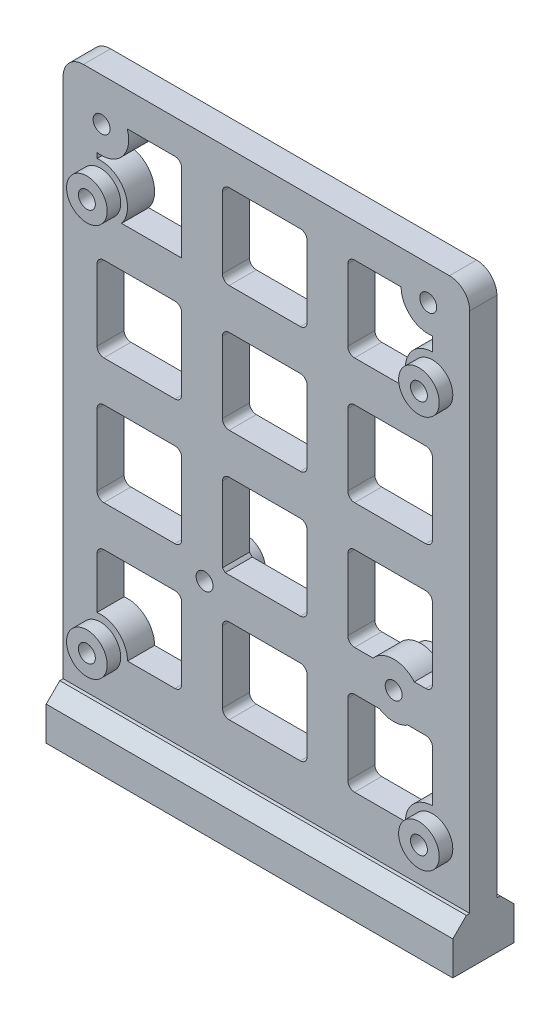
SolidWorks part; units mm, degrees
ref_plane "Спереди" through (0, 0, 0) normal (0, 0, 1) x (1, 0, 0)
ref_plane "Сверху" through (0, 0, 0) normal (0, 1, 0) x (1, 0, 0)
ref_plane "Справа" through (0, 0, 0) normal (1, 0, 0) x (0, 0, -1)
sketch "Sketch1" plane through (0, 0, 0) normal (0, 0, 1) x (1, 0, 0)
  line L1 (-30, 40) -> (30, 40)
  line L2 (-30, 40) -> (-30, -40)
  line L3 (-30, -40) -> (30, -40)
  line L4 (30, 40) -> (30, -40)
  line L5 (-30, 40) -> (30, -40) construction
  line L6 (-30, -40) -> (30, 40) construction
  point P0 (0, 0)
  dimension "D1" = 80
  dimension "D2" = 60
extrude "Boss-Extrude1" add sketch "Sketch1" along normal blind 4
sketch "Sketch2" plane through (0, 0, 4) normal (0, 0, 1) x (1, 0, 0)
  line L0 (0, 17.2836) -> (0, -4) construction
  line L1 (0, -4) -> (-11.1351, -4) construction
  line L2 (30, 40) -> (-30, 40) construction
  circle A0 centre (-24.5, 25) radius 1.25
  circle A1 centre (24.5, 25) radius 1.25
  circle A2 centre (24.5, -33) radius 1.25
  circle A3 centre (-24.5, -33) radius 1.25
  point P12 (-24.5, 32.5822)
  dimension "D1" = 58
  dimension "D2" = 49
  dimension "D3" = 2.5
  dimension "D4" = 15
extrude "Cut-Extrude1" cut sketch "Sketch2" against normal through all
sketch "Sketch3" plane through (0, 0, 4) normal (0, 0, 1) x (1, 0, 0)
  circle A0 centre (-24.5, 25) radius 3
  circle A1 centre (24.5, 25) radius 3
  circle A2 centre (24.5, -33) radius 3
  circle A3 centre (-24.5, -33) radius 3
  point P5 (24.5, 32.5)
  point P9 (24.5, -25.5)
  point P13 (-24.5, -25.5)
  circle M5 centre (-24.5, -33) radius 1.25
  circle M6 centre (24.5, -33) radius 1.25
  circle M7 centre (24.5, 25) radius 1.25
  circle M8 centre (-24.5, 25) radius 1.25
  dimension "D1" = 6
extrude "Boss-Extrude2" add sketch "Sketch3" along normal blind 2 contours A0 M8 | A1 M7 | A2 M6 | A3 M5
sketch "Sketch4" plane through (0, 0, 0) normal (0, 0, -1) x (-1, 0, 0)
  line L1 (-30, 40) -> (30, 40) construction
  circle A0 centre (-18.7727, -17.1) radius 1.25
  circle A1 centre (9.1273, -17.1) radius 1.25
  circle A2 centre (-23.8727, 35) radius 1.25
  circle A3 centre (24.3273, 33.7) radius 1.25
  point P4 (23.4203, 17.4097)
  point P9 (9.1273, -30.7292)
  dimension "D1" = 2.5
  dimension "D2" = 2.5
  dimension "D3" = 27.9
  dimension "D4" = 2.5
  dimension "D5" = 5.1
  dimension "D7" = 2.5
  dimension "D6" = 52.1
  dimension "D8" = 1.3
  dimension "D9" = 15.2
  dimension "D10" = 5
extrude "Cut-Extrude2" cut sketch "Sketch4" against normal through all
sketch "Sketch5" plane through (0, 0, 0) normal (0, 0, -1) x (-1, 0, 0)
  circle A0 centre (-23.8727, 35) radius 3
  circle A1 centre (24.3273, 33.7) radius 3
  circle A2 centre (-18.7727, -17.1) radius 3
  circle A3 centre (9.1273, -17.1) radius 3
  circle M1 centre (24.3273, 33.7) radius 1.25
  circle M2 centre (-23.8727, 35) radius 1.25
  circle M3 centre (9.1273, -17.1) radius 1.25
  circle M4 centre (-18.7727, -17.1) radius 1.25
  dimension "D1" = 6
  dimension "D2" = 6
  dimension "D3" = 6
  dimension "D4" = 6
extrude "Boss-Extrude3" add sketch "Sketch5" along normal blind 2 contours A0 M2 | A1 M1 | A3 M3 | A2 M4
sketch "Sketch7" plane through (0, 0, 4) normal (0, 0, 1) x (1, 0, 0)
  line L0 (-30, 40) -> (-30, -40) construction
  line L1 (-25, 35) -> (-12.5, 35)
  line L2 (-25, 35) -> (-25, 22.5)
  line L3 (-25, 22.5) -> (-12.5, 22.5)
  line L4 (-12.5, 35) -> (-12.5, 22.5)
  line L5 (30, 40) -> (-30, 40) construction
  line L6 (-6.5, 35) -> (-6.5, 22.5)
  line L7 (-6.5, 35) -> (6, 35)
  line L8 (6, 35) -> (6, 22.5)
  line L9 (-6.5, 22.5) -> (6, 22.5)
  line L10 (12, 35) -> (12, 22.5)
  line L11 (12, 35) -> (24.5, 35)
  line L12 (24.5, 35) -> (24.5, 22.5)
  line L13 (12, 22.5) -> (24.5, 22.5)
  line L14 (-6.5, 16.5) -> (-6.5, 4)
  line L15 (-6.5, 16.5) -> (6, 16.5)
  line L16 (6, 16.5) -> (6, 4)
  line L17 (-6.5, 4) -> (6, 4)
  line L18 (12, 16.5) -> (12, 4)
  line L19 (12, 16.5) -> (24.5, 16.5)
  line L20 (24.5, 16.5) -> (24.5, 4)
  line L21 (12, 4) -> (24.5, 4)
  line L22 (-6.5, -2) -> (-6.5, -14.5)
  line L23 (-6.5, -2) -> (6, -2)
  line L24 (6, -2) -> (6, -14.5)
  line L25 (-6.5, -14.5) -> (6, -14.5)
  line L26 (12, -2) -> (12, -14.5)
  line L27 (12, -2) -> (24.5, -2)
  line L28 (24.5, -2) -> (24.5, -14.5)
  line L29 (12, -14.5) -> (24.5, -14.5)
  line L30 (-6.5, -20.5) -> (-6.5, -33)
  line L31 (-6.5, -20.5) -> (6, -20.5)
  line L32 (6, -20.5) -> (6, -33)
  line L33 (-6.5, -33) -> (6, -33)
  line L34 (12, -20.5) -> (12, -33)
  line L35 (12, -20.5) -> (24.5, -20.5)
  line L36 (24.5, -20.5) -> (24.5, -33)
  line L37 (12, -33) -> (24.5, -33)
  line L38 (-25, 16.5) -> (-25, 4)
  line L39 (-25, 16.5) -> (-12.5, 16.5)
  line L40 (-12.5, 16.5) -> (-12.5, 4)
  line L41 (-25, 4) -> (-12.5, 4)
  line L42 (-25, -2) -> (-25, -14.5)
  line L43 (-25, -2) -> (-12.5, -2)
  line L44 (-12.5, -2) -> (-12.5, -14.5)
  line L45 (-25, -14.5) -> (-12.5, -14.5)
  line L46 (-25, -20.5) -> (-25, -33)
  line L47 (-25, -20.5) -> (-12.5, -20.5)
  line L48 (-12.5, -20.5) -> (-12.5, -33)
  line L49 (-25, -33) -> (-12.5, -33)
  circle A0 centre (-24.3273, 33.7) radius 4
  circle A1 centre (-24.5, 25) radius 4
  circle A2 centre (24.5, 25) radius 4
  circle A3 centre (23.8727, 35) radius 4
  circle A4 centre (-9.1273, -17.1) radius 4
  circle A5 centre (18.7727, -17.1) radius 4
  circle A6 centre (24.5, -33) radius 4
  circle A7 centre (-24.5, -33) radius 4
  dimension "D6" = 8
  dimension "D7" = 8
  dimension "D8" = 8
  dimension "D9" = 8
  dimension "D10" = 8
  dimension "D11" = 8
  dimension "D12" = 8
  dimension "D13" = 8
  dimension "D1" = 12.5
  dimension "D2" = 5
  dimension "D3" = 5
  dimension "D4" = 3
  dimension "D5" = 4
extrude "Cut-Extrude4" cut sketch "Sketch7" against normal blind 4 contours A7 L49 L48 L47 L46 | L30 L33 L32 L31 | A6 L36 L35 A5 L34 L37 | A5 L29 L28 L27 L26 | A4 L25 L24 L23 L22 | L42 L45 L44 L43 | L38 L41 L40 L39 | L14 L17 L16 L15 | L18 L21 L20 L19 | A1 L3 L4 L1 A0 L2 | L6 L9 L8 L7 | A3 L11 L10 L13 A2 L12
fillet "Fillet3" radius 1 40 edges at (24.5, -20.5, 2) (12, 35, 2) (12, 16.5, 2) (12, -20.5, 2) (12, -2, 2) (12, -14.5, 2) (12, -33, 2) (-6.5, -33, 2) (-25, -14.5, 2) (-6.5, 22.5, 2) (12, 22.5, 2) (12, 4, 2) (-6.5, 35, 2) (-6.5, -20.5, 2) (-6.5, -2, 2) (-6.5, 16.5, 2) (-25, -2, 2) (-25, -20.5, 2) (6, 16.5, 2) (6, 35, 2) (24.5, 16.5, 2) (24.5, -2, 2) (6, -20.5, 2) (-12.5, -20.5, 2) (-12.5, -2, 2) (6, 22.5, 2) (24.5, 4, 2) (24.5, -14.5, 2) (-12.5, -14.5, 2) (-12.5, -33, 2) (6, -33, 2) (6, -14.5, 2) (6, 4, 2) (-12.5, 4, 2) (-12.5, 35, 2) (-12.5, 16.5, 2) (-25, 16.5, 2) (-25, 4, 2) (6, -2, 2) (-6.5, 4, 2)
fillet "Fillet2" radius 3 2 edges at (30, 40, 2) (-30, 40, 2)
sketch "Sketch8" plane through (0, -40, 0) normal (0, -1, 0) x (1, 0, 0)
  line L0 (-30, 4) -> (-30, 0) construction
  line L1 (-30, 6.5) -> (30, 6.5)
  line L2 (-30, 6.5) -> (-30, -2.5)
  line L3 (-30, -2.5) -> (30, -2.5)
  line L4 (30, 6.5) -> (30, -2.5)
  line L5 (30, 4) -> (30, 0) construction
  line L6 (-30, 4) -> (30, 4) construction
  dimension "D1" = 9
  dimension "D2" = 2.5
extrude "Boss-Extrude4" add sketch "Sketch8" along normal blind 7
chamfer "Chamfer1" distance 2 angle 45 2 edges at (0, -40, -2.5) (0, -40, 6.5)
sketch "Sketch9" plane through (0, -47, 0) normal (0, -1, 0) x (1, 0, 0)
  line L0 (-30, 2) -> (-4.1301, 2) construction
  line L1 (-30, 6.5) -> (-30, -2.5) construction
  line L2 (0, 0) -> (0, 9.4521) construction
  circle A0 centre (-22.5, 2) radius 1.45
  circle A1 centre (22.5, 2) radius 1.45
  dimension "D1" = 2.9
  dimension "D2" = 45
extrude "Cut-Extrude5" cut sketch "Sketch9" against normal blind 8
